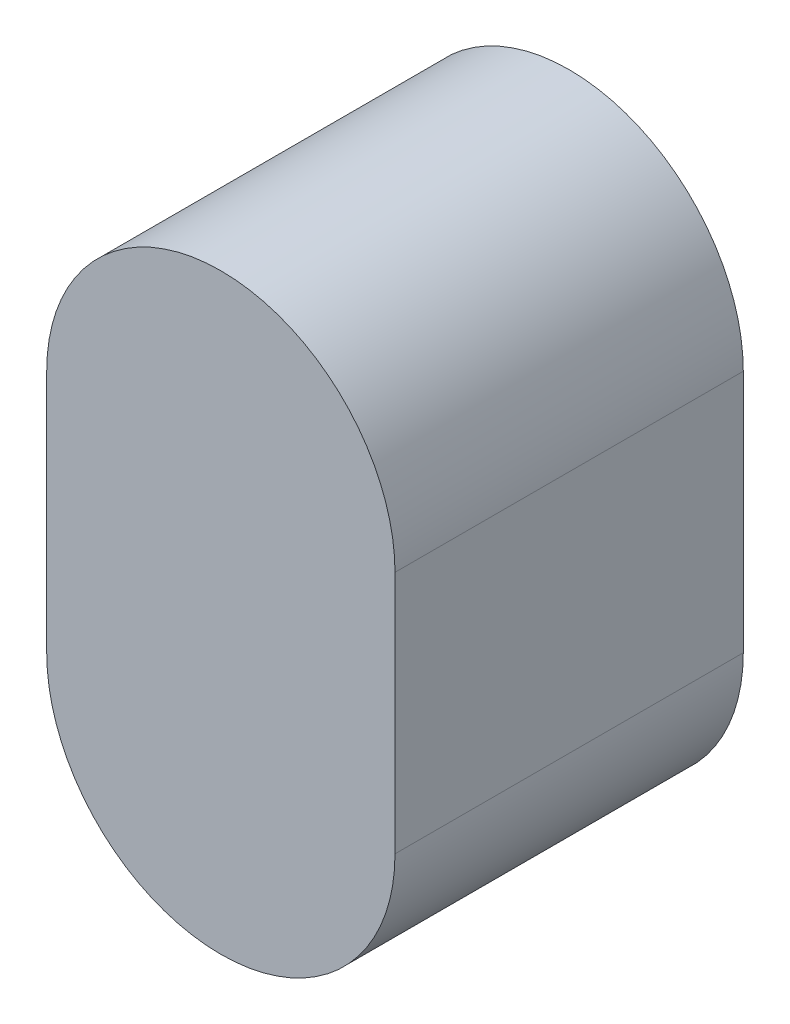
SolidWorks part; units mm, degrees
ref_plane "Płaszczyzna przednia" through (0, 0, 0) normal (0, 0, 1) x (1, 0, 0)
ref_plane "Płaszczyzna górna" through (0, 0, 0) normal (0, 1, 0) x (1, 0, 0)
ref_plane "Płaszczyzna prawa" through (0, 0, 0) normal (1, 0, 0) x (0, 0, -1)
sketch "Szkic1" plane through (0, 0, 0) normal (0, 0, 1) x (1, 0, 0)
  line L0 (0, 0) -> (0, 3.5) construction
  line L1 (-2.5, 0) -> (-2.5, 3.5)
  line L2 (2.5, 0) -> (2.5, 3.5)
  arc A0 (-2.5, 0) -> (2.5, 0) centre (0, 0) ccw
  arc A1 (2.5, 3.5) -> (-2.5, 3.5) centre (0, 3.5) ccw
  point P3 (0, 1.75)
  dimension "D1" = 3.5
  dimension "D2" = 5
extrude "Dodanie-wyciągnięcie1" add sketch "Szkic1" along normal blind 5
